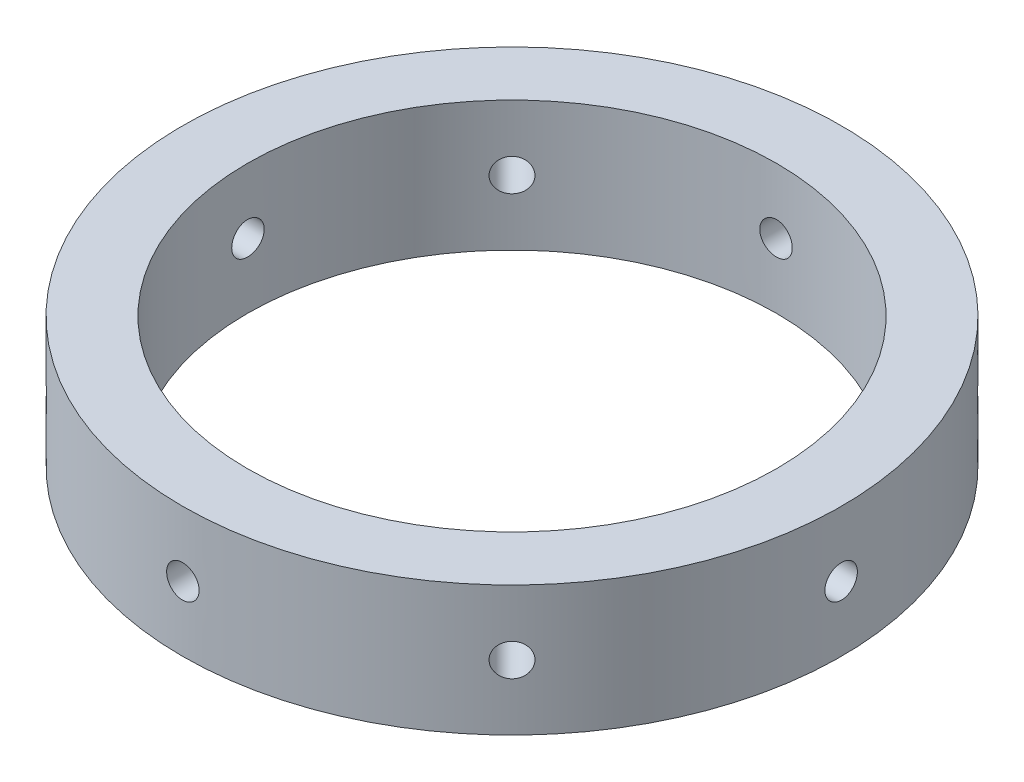
SolidWorks part; units mm, degrees
ref_plane "Front Plane" through (0, 0, 0) normal (0, 0, 1) x (1, 0, 0)
ref_plane "Top Plane" through (0, 0, 0) normal (0, 1, 0) x (1, 0, 0)
ref_plane "Right Plane" through (0, 0, 0) normal (1, 0, 0) x (0, 0, -1)
sketch "Sketch3" plane through (0, 0, 0) normal (0, 1, 0) x (1, 0, 0)
  circle A0 centre (0, 0) radius 50.7
  circle A1 centre (0, 0) radius 40.7
  dimension "D1" = 101.4
  dimension "D2" = 81.4
extrude "Boss-Extrude1" add sketch "Sketch3" along normal blind 20
ref_plane "Plane2" through (50.7, 0, 0) normal (1, 0, 0) x (0, 0, -1)
sketch "Sketch5" plane through (50.7, 0, 0) normal (1, 0, 0) x (0, 0, -1)
  line L0 (0, 0) -> (0, 20) construction
  line L1 (40.7, 20) -> (-40.7, 20) construction
  line L2 (-55.8566, 10) -> (-56.1948, 10) construction
  line L3 (-56.1948, 10) -> (55.6312, 10) construction
  circle A0 centre (0, 10) radius 2.5
  dimension "D1" = 5
extrude "Cut-Extrude1" cut sketch "Sketch5" against normal up to next
pattern_circular "CirPattern1" count 8 over 360 about axis through (0, 20, 0) along (0, -1, 0) of "Cut-Extrude1"
equation "\"circulo grande\"= 101.4mm"
equation "\"D1@Sketch3\"=\"circulo grande\""
equation "\"circulo pequeño\" = 81.4mm"
equation "\"D2@Sketch3\"=\"circulo pequeño\""
equation "\"ancho\" = 20mm"
equation "\"Boss-Extrude1@Boss-Extrude1\"=\"ancho\""
equation "\"circulo tornillo\" = 5mm"
equation "\"D1@Sketch5\"=\"circulo tornillo\""
